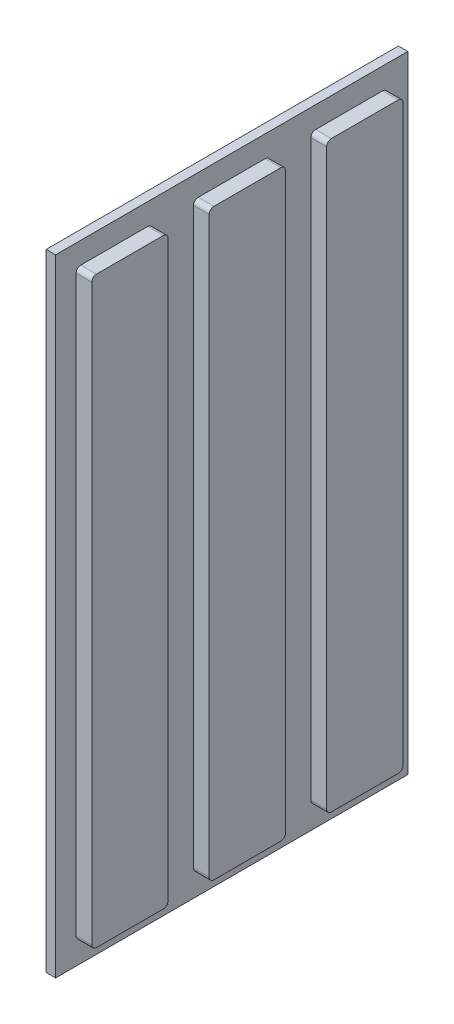
SolidWorks part; units mm, degrees
ref_plane "Front Plane" through (0, 0, 0) normal (1, 0, 0) x (0, 1, 0)
ref_plane "Top Plane" through (0, 0, 0) normal (0, 0, 1) x (0, 1, 0)
ref_plane "Right Plane" through (0, 0, 0) normal (0, 1, 0) x (-1, 0, 0)
sketch "Sketch1" plane through (0, 0, 0) normal (1, 0, 0) x (0, 1, 0)
  line L1 (40, -22.5) -> (-40, -22.5)
  line L2 (40, -22.5) -> (40, 22.5)
  line L3 (40, 22.5) -> (-40, 22.5)
  line L4 (-40, -22.5) -> (-40, 22.5)
  line L5 (40, -22.5) -> (-40, 22.5) construction
  line L6 (40, 22.5) -> (-40, -22.5) construction
  point P0 (0, 0)
  dimension "D1" = 80
  dimension "D2" = 45
extrude "Boss-Extrude1" add sketch "Sketch1" against normal blind 1.2
sketch "Sketch2" plane through (0, 0, 0) normal (1, 0, 0) x (0, 1, 0)
  line L0 (0, -1.76) -> (0, 1.76) construction
  line L1 (37.25, 10.125) -> (-37.25, 10.125)
  line L2 (37.25, 10.125) -> (37.25, 19.875)
  line L3 (37.25, 19.875) -> (-37.25, 19.875)
  line L4 (-37.25, 10.125) -> (-37.25, 19.875)
  line L5 (37.25, 10.125) -> (-37.25, 19.875) construction
  line L6 (37.25, 19.875) -> (-37.25, 10.125) construction
  line L7 (40, 22.5) -> (-40, 22.5) construction
  point P0 (0, 15)
  dimension "D1" = 74.5
  dimension "D2" = 9.75
  dimension "D3" = 7.5
extrude "Boss-Extrude2" add sketch "Sketch2" along normal blind 2
ref_plane "Plane1" through (0, 0, 15) normal (0, 0, 1) x (0, -1, 0)
pattern_linear "LPattern1" count 3 spacing 15 along (0, 0, -1) of "Boss-Extrude2"
sketch "Sketch3" plane through (-1.2, 0, 0) normal (-1, 0, 0) x (0, -1, 0)
  line L0 (-40, 4.875) -> (40, 4.875) construction
  line L3 (-37.25, 4.875) -> (37.25, 4.875) construction
  text T0 "<b>92223061_B</b>" font "Century Gothic" height 3.5
extrude "Cut-Extrude1" cut sketch "Sketch3" against normal blind 0.6
fillet "Fillet1" radius 0.6 12 edges at (1, 37.25, -4.875) (1, 37.25, 4.875) (1, -37.25, -4.875) (1, -37.25, 4.875) (1, -37.25, -19.875) (1, -37.25, -10.125) (1, 37.25, -19.875) (1, 37.25, -10.125) (1, 37.25, 10.125) (1, 37.25, 19.875) (1, -37.25, 10.125) (1, -37.25, 19.875)
